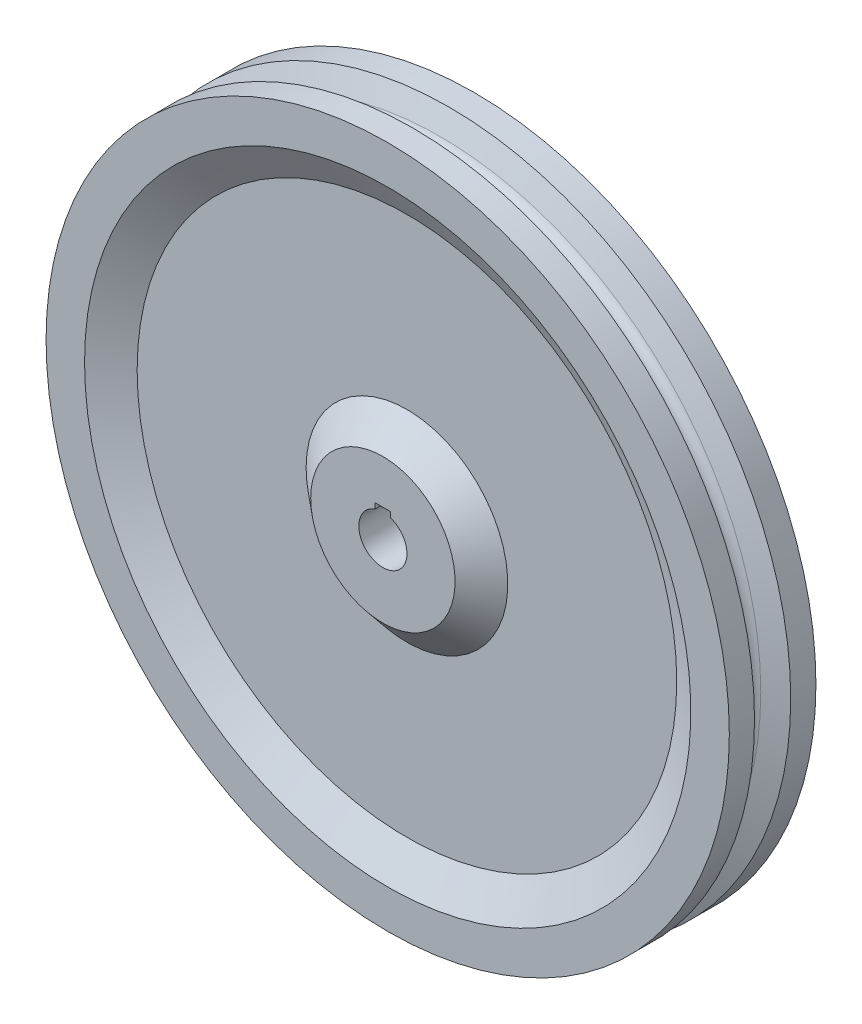
SolidWorks part; units mm, degrees
ref_plane "Plan de face" through (0, 0, 0) normal (0, 0, 1) x (1, 0, 0)
ref_plane "Plan de dessus" through (0, 0, 0) normal (0, 1, 0) x (1, 0, 0)
ref_plane "Plan de droite" through (0, 0, 0) normal (1, 0, 0) x (0, 0, -1)
sketch "Esquisse1" plane through (0, 0, 0) normal (1, 0, 0) x (0, 0, -1)
  line L0 (0, 0) -> (-50, 0)
  line L1 (-50, 0) -> (-50, 75)
  line L2 (-50, 75) -> (-25, 104.7938)
  line L3 (-25, 104.7938) -> (-25, 280.359)
  line L4 (-25, 280.359) -> (-45, 315)
  line L5 (-45, 315) -> (-45, 355)
  line L6 (-45, 355) -> (-18.821, 355)
  line L7 (-18.821, 355) -> (-9.7007, 332.9818)
  line L8 (0, 326.5) -> (0, 0)
  line L10 (0, 326.5) -> (32.0144, 326.5) construction
  arc A1 (-9.7007, 332.9818) -> (0, 326.5) centre (0, 337) ccw
  dimension "D5" = 10.5
  dimension "D1" = 50
  dimension "D2" = 25
  dimension "D3" = 45
  dimension "D4" = 28.5
  dimension "D6" = 67.5
  dimension "D7" = 40
  dimension "D8" = 30
  dimension "D9" = 75
  dimension "D10" = 355
  dimension "D11" = 40
revolve "Révolution1" add sketch "Esquisse1" angle 360 about L0
mirror "Symétrie1" about plane through (0, 326.5, 0) normal (0, 0, -1) of "Révolution1"
sketch "Esquisse2" plane through (0, 0, 50) normal (0, 0, 1) x (1, 0, 0)
  circle A0 centre (0, 0) radius 25
  dimension "D1" = 50
extrude "Enlèv. mat.-Extru.1" cut sketch "Esquisse2" against normal through all
sketch "Esquisse3" plane through (0, 0, 50) normal (0, 0, 1) x (1, 0, 0)
  line L0 (0, 0) -> (0, 25) construction
  line L2 (8, 20.7) -> (-8, 20.7)
  line L3 (8, 20.7) -> (8, 29.3)
  line L4 (8, 29.3) -> (-8, 29.3)
  line L5 (-8, 20.7) -> (-8, 29.3)
  line L6 (8, 20.7) -> (-8, 29.3) construction
  line L7 (8, 29.3) -> (-8, 20.7) construction
  circle A0 centre (0, 0) radius 25 construction
  dimension "D1" = 16
  dimension "D2" = 8.6
extrude "Enlèv. mat.-Extru.2" cut sketch "Esquisse3" against normal through all
scale "Echelle1" scale about centroid uniform scaling yes scale factor 0.5
